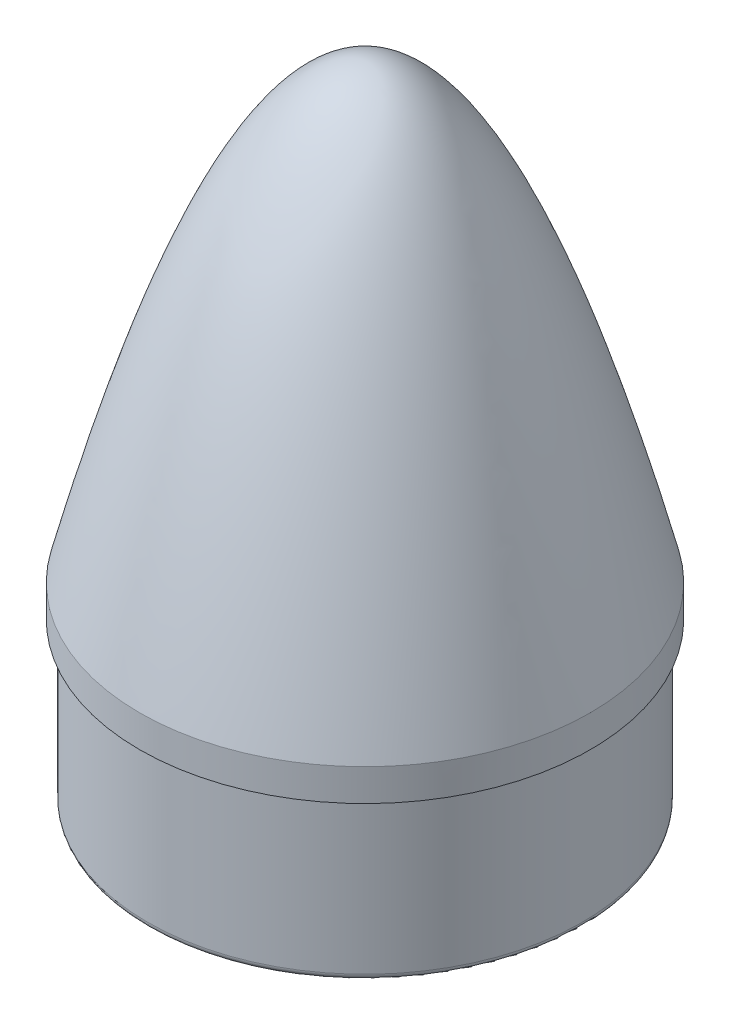
SolidWorks part; units mm, degrees
ref_plane "Piano frontale"
ref_plane "Piano superiore" through (0, 0, 0) normal (0, 1, 0) x (1, 0, 0)
ref_plane "Piano destro" through (0, 0, 0) normal (1, 0, 0) x (0, 0, -1)
sketch "Schizzo1" plane through (0, 0, 0) normal (0, 0, 1) x (1, 0, 0)
  line L1 (0, 141) -> (0, 0)
  line L3 (0, 0) -> (0, -10)
  line L4 (70.5, 0) -> (70.5, -10)
  line L5 (70.5, -10) -> (68, -10)
  line L6 (68, -10) -> (68, -58)
  line L7 (66, -60) -> (0, -60)
  line L8 (0, -60) -> (0, -10)
  arc A0 (68, -58) -> (66, -60) centre (66, -58) cw
  spline S0 degree 2 poles (-7.05, 139.59) (33.664, 155.8756) (74.3781, -15.939) knots 0 0 0 1 1 1 construction
  spline S1 degree 2 poles (0, 141) (35.25, 141) (70.5, 0) knots 0.086579 0.086579 0.086579 0.952374 0.952374 0.952374
  point P15 (68, -60)
revolve "Rivoluzione3" add sketch "Schizzo1" angle 360 about L1
sketch "Schizzo6" plane through (0, -60, 0) normal (0, -1, 0) x (1, 0, 0)
  circle A0 centre (0, 0) radius 66
ref_plane "Piano1" through (0, 141, 0) normal (0, -1, 0) x (-1, 0, 0)
